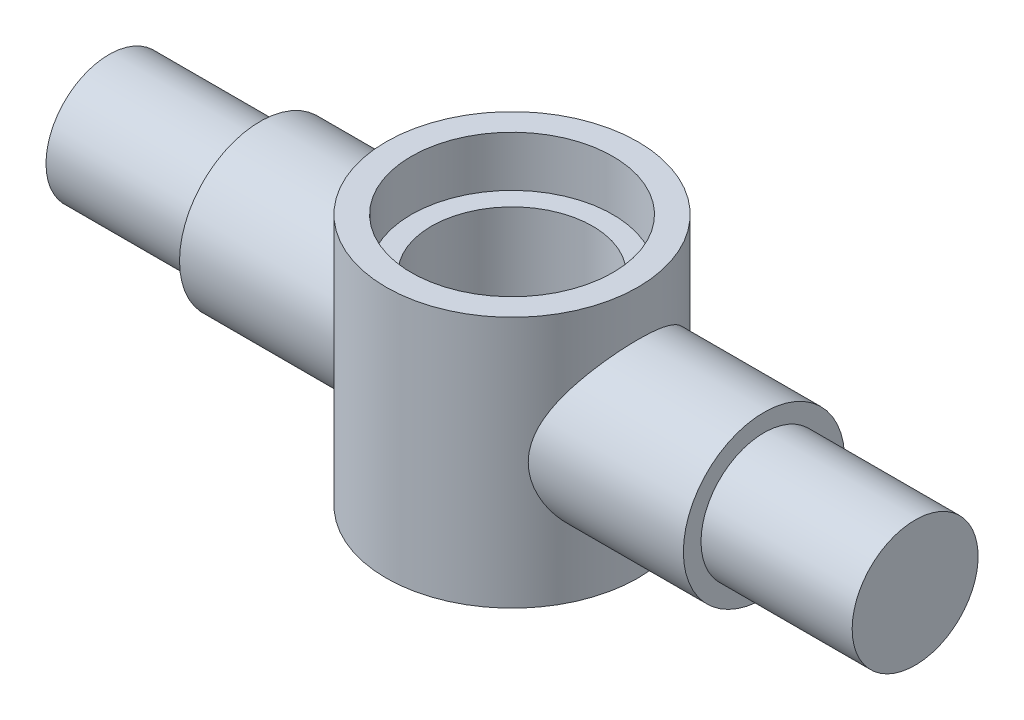
SolidWorks part; units mm, degrees
ref_plane "Front Plane" through (0, 0, 0) normal (0, 0, 1) x (1, 0, 0)
ref_plane "Top Plane" through (0, 0, 0) normal (0, 1, 0) x (1, 0, 0)
ref_plane "Right Plane" through (0, 0, 0) normal (1, 0, 0) x (0, 0, -1)
sketch "Sketch1" plane through (0, 0, 0) normal (0, 0, 1) x (1, 0, 0)
  line L0 (0, 25) -> (0, -25)
  line L1 (0, -25) -> (25, -25)
  line L2 (25, -25) -> (25, 25)
  line L3 (25, 25) -> (0, 25)
  dimension "D1" = 25
  dimension "D2" = 50
  dimension "D3" = 25
revolve "Revolve1" add sketch "Sketch1" angle 360 about L0
sketch "Sketch2" plane through (0, 0, 0) normal (0, 0, 1) x (1, 0, 0)
  line L0 (-80, 0) -> (80, 0)
  line L1 (80, 0) -> (80, 12.5)
  line L2 (80, 12.5) -> (50, 12.5)
  line L3 (50, 12.5) -> (50, 16)
  line L4 (50, 16) -> (-50, 16)
  line L5 (0, -27.5) -> (0, 27.5) construction
  line L6 (-80, 0) -> (-80, 12.5)
  line L7 (-80, 12.5) -> (-50, 12.5)
  line L8 (-50, 12.5) -> (-50, 16)
  point P0 (0, 16)
  point P3 (0, 0)
  point P8 (0, 0)
  point P15 (0, 0)
  dimension "D1" = 12.5
  dimension "D2" = 16
  dimension "D3" = 80
  dimension "D4" = 50
revolve "Revolve2" add sketch "Sketch2" angle 360 about L0
sketch "Sketch3" plane through (0, 0, 0) normal (0, 0, 1) x (1, 0, 0)
  line L0 (0, 25) -> (0, -25)
  line L1 (25, 25) -> (-25, 25) construction
  line L2 (0, -25) -> (16, -25)
  line L3 (-25, -25) -> (25, -25) construction
  line L4 (16, -25) -> (16, 15)
  line L5 (16, 15) -> (20, 15)
  line L6 (20, 15) -> (20, 25)
  line L7 (20, 25) -> (0, 25)
  dimension "D1" = 16
  dimension "D2" = 20
  dimension "D3" = 10
revolve "Cut-Revolve1" cut sketch "Sketch3" angle 360 about L0
